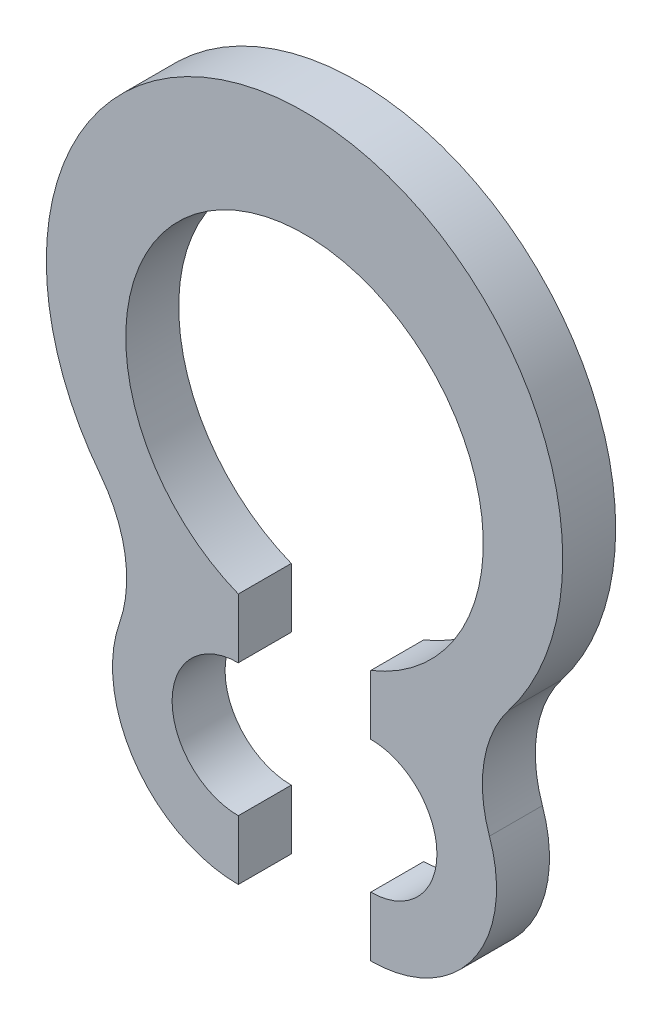
SolidWorks part; units mm, degrees
ref_plane "Front" through (0, 0, 0) normal (0, 0, 1) x (1, 0, 0)
ref_plane "Top" through (0, 0, 0) normal (0, 1, 0) x (1, 0, 0)
ref_plane "Right" through (0, 0, 0) normal (1, 0, 0) x (0, 0, -1)
sketch "Sketch1" plane through (0, 0, 0) normal (0, 0, 1) x (1, 0, 0)
  line L0 (0, -0.2) -> (0, -3.1859) construction
  line L1 (-0.5, -1.454) -> (-0.5, -1.904)
  line L2 (-0.5, -2.904) -> (-0.5, -3.354)
  line L3 (0.5, -2.904) -> (0.5, -3.354)
  line L4 (0.5, -1.454) -> (0.5, -1.904)
  arc A0 (0.5, -1.454) -> (-0.5, -1.454) centre (0, -0.2) ccw
  arc A1 (1.5419, -1.1938) -> (-1.5419, -1.1938) centre (0, 0) ccw
  arc A2 (-0.5, -1.904) -> (-0.5, -2.904) centre (-0.5, -2.404) ccw
  arc A3 (-0.5, -3.354) -> (-1.3965, -2.0897) centre (-0.5, -2.404) cw
  arc A4 (-1.5419, -1.1938) -> (-1.3965, -2.0897) centre (-2.293, -1.7754) cw
  arc A5 (1.5419, -1.1938) -> (1.3965, -2.0897) centre (2.293, -1.7754) ccw
  arc A6 (0.5, -3.354) -> (1.3965, -2.0897) centre (0.5, -2.404) ccw
  arc A7 (0.5, -1.904) -> (0.5, -2.904) centre (0.5, -2.404) cw
  dimension "d" = 2.7
  dimension "D0" = 3.9
  dimension "R3" = 0.95
  dimension "c" = 0.2
  dimension "B1" = 1
  dimension "d1" = 1
  dimension "h" = 0.95
  dimension "D2" = 1
extrude "Body" add sketch "Sketch1" against normal blind 0.4 separate body
equation "\"D2@Sketch1\" = \"d1@Sketch1\""
equation "\"R3@Sketch1\" = \"h@Sketch1\""
